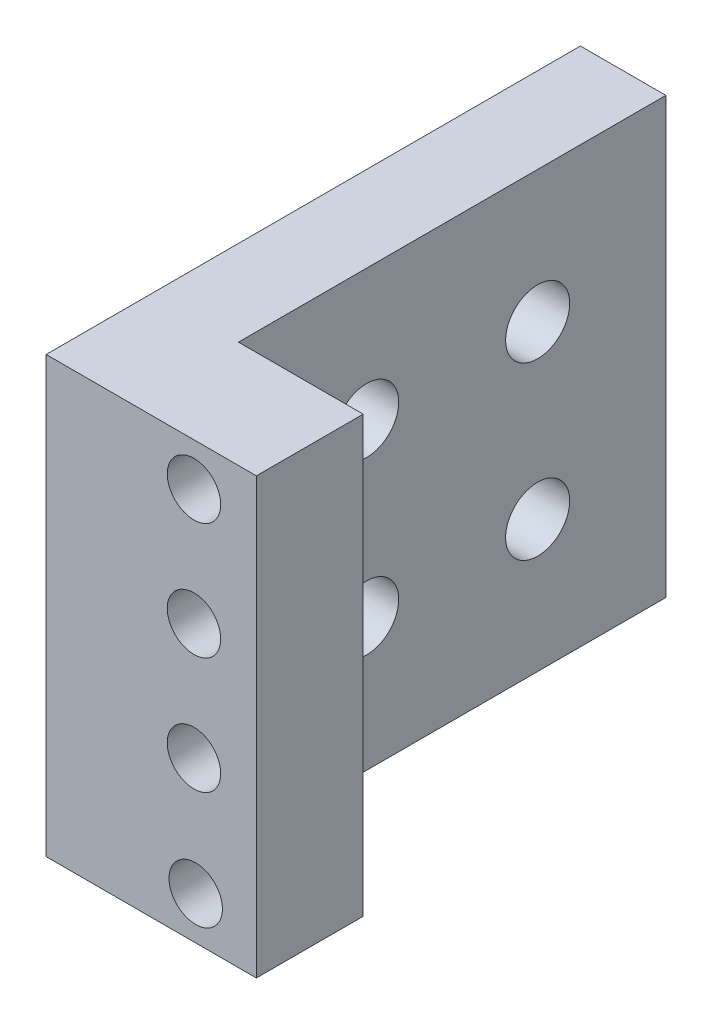
SolidWorks part; units mm, degrees
ref_plane "前视基准面" through (0, 0, 0) normal (0, 0, 1) x (1, 0, 0)
ref_plane "上视基准面" through (0, 0, 0) normal (0, 1, 0) x (1, 0, 0)
ref_plane "右视基准面" through (0, 0, 0) normal (1, 0, 0) x (0, 0, -1)
sketch "草图1" plane through (0, 0, 0) normal (0, 0, 1) x (1, 0, 0)
  line L0 (-3, -8.028) -> (-3, -12.6119)
  line L1 (-3, 7.7375) -> (2.8377, 7.7375)
  line L2 (-3, 7.7375) -> (-3, -8.028)
  line L4 (2.8377, 7.7375) -> (2.8377, -6.6419)
  line L5 (-0.0812, -9) -> (-0.0812, 7.028) construction
  line L6 (-3, -0.1452) -> (3, -0.1452) construction
  line L7 (-3, -12.6119) -> (2.8377, -12.6119)
  line L8 (2.8377, -12.6119) -> (2.8377, -6.6419)
  circle A0 centre (-0.0812, 5.7375) radius 1.25
  circle A1 centre (-0.0812, 0.2875) radius 1.25
  circle A2 centre (-0.0812, -5.1625) radius 1.25
  circle A3 centre (-0.0008, -10.6119) radius 1.25
  point P0 (0, 0)
  dimension "D3" = 2.5
  dimension "D4" = 2.5
  dimension "D5" = 2.5
  dimension "D1" = 2.5
  dimension "D2" = 6
  dimension "D6" = 5.45
  dimension "D7" = 2
  dimension "D8" = 5.45
  dimension "D9" = 5.45
  dimension "D10" = 2
extrude "凸台-拉伸1" add sketch "草图1" along normal blind 5
sketch "草图2" plane through (-3, 0, 0) normal (-1, 0, 0) x (0, 0, 1)
  line L1 (0, 7.7375) -> (5, 7.7375)
  line L2 (0, 7.7375) -> (0, -12.6119)
  line L3 (0, -12.6119) -> (5, -12.6119)
  line L4 (5, 7.7375) -> (5, -12.6119)
extrude "凸台-拉伸2" add sketch "草图2" along normal blind 4
sketch "草图3" plane through (0, 0, 0) normal (0, 0, -1) x (-1, 0, 0)
  line L0 (-2.8377, 7.7375) -> (7, 7.7375) construction
  line L1 (3, 7.7375) -> (7, 7.7375)
  line L2 (3, 7.7375) -> (3, -12.6119)
  line L3 (3, -12.6119) -> (7, -12.6119)
  line L4 (7, 7.7375) -> (7, -12.6119)
  line L5 (7, 7.7375) -> (7, -12.6119) construction
  line L6 (7, -12.6119) -> (-2.8377, -12.6119) construction
  dimension "D1" = 4
extrude "凸台-拉伸3" add sketch "草图3" along normal blind 20 contours L2 L1 L4 L3
sketch "草图4" plane through (-3, 0, 0) normal (1, 0, 0) x (0, 0, -1)
  line L0 (-0.5142, -2.4372) -> (22.6758, -2.4372) construction
  line L1 (10, 9.3991) -> (10, -15.8743) construction
  circle A0 centre (6, 1.5628) radius 1.5
  circle A1 centre (14, 1.5628) radius 1.5
  circle A2 centre (14, -6.4372) radius 1.5
  circle A3 centre (6, -6.4372) radius 1.5
  dimension "D1" = 3
  dimension "D2" = 4
  dimension "D3" = 4
extrude "切除-拉伸1" cut sketch "草图4" against normal blind 20
